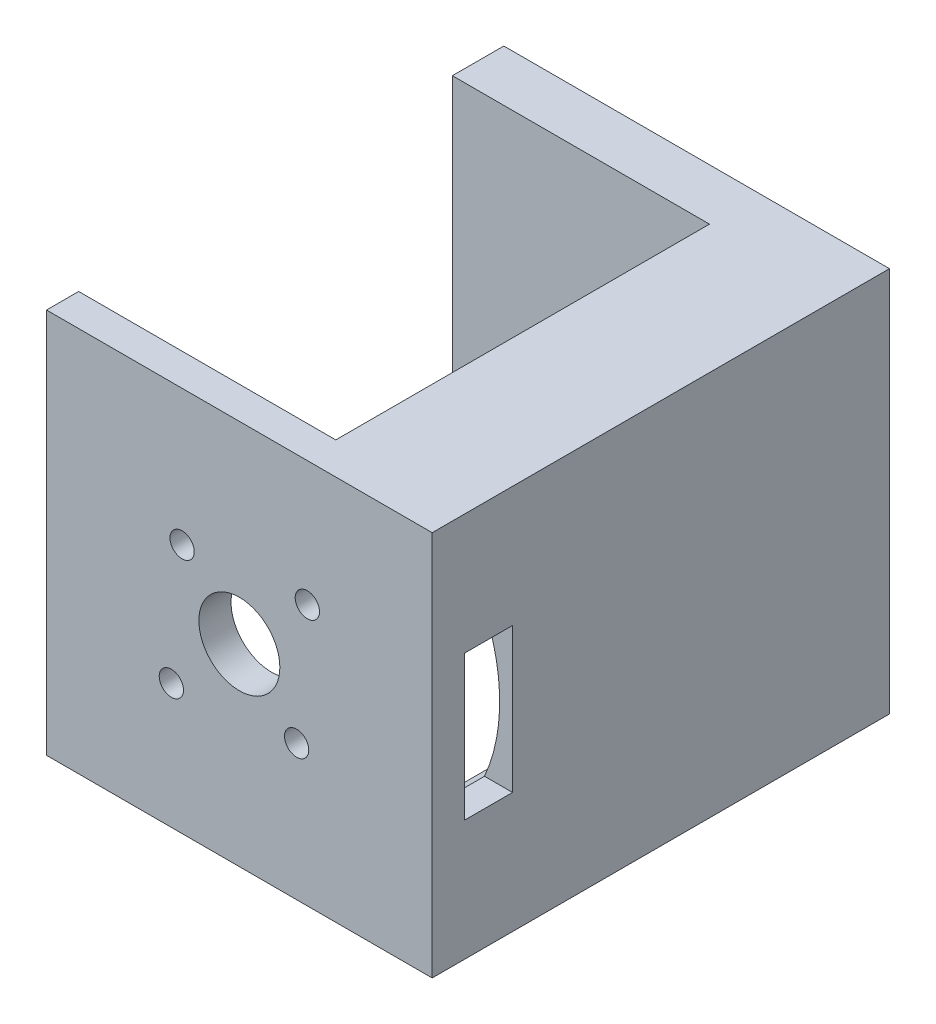
SolidWorks part; units mm, degrees
ref_plane "Front Plane" through (0, 0, 0) normal (0, 0, 1) x (1, 0, 0)
ref_plane "Top Plane" through (0, 0, 0) normal (0, 1, 0) x (1, 0, 0)
ref_plane "Right Plane" through (0, 0, 0) normal (1, 0, 0) x (0, 0, -1)
sketch "Sketch2" plane through (0, 0, 0) normal (0, 0, 1) x (1, 0, 0)
  line L0 (0, 0) -> (19.05, 0) construction
  line L1 (-19.05, 19.05) -> (19.05, 19.05)
  line L2 (-19.05, 19.05) -> (-19.05, -19.05)
  line L3 (-19.05, -19.05) -> (19.05, -19.05)
  line L4 (19.05, 19.05) -> (19.05, -19.05)
  line L5 (0, 0) -> (0, 19.05) construction
  arc A0 (5.5175, 6.7175) -> (7.9175, 6.7175) centre (6.7175, 6.7175) ccw construction
  arc A1 (7.9175, 6.7175) -> (5.5175, 6.7175) centre (6.7175, 6.7175) ccw construction
  arc A2 (4.4569, -5.6569) -> (6.8569, -5.6569) centre (5.6569, -5.6569) ccw construction
  arc A3 (6.8569, -5.6569) -> (4.4569, -5.6569) centre (5.6569, -5.6569) ccw construction
  arc A4 (-7.9175, -6.7175) -> (-5.5175, -6.7175) centre (-6.7175, -6.7175) ccw construction
  arc A5 (-5.5175, -6.7175) -> (-7.9175, -6.7175) centre (-6.7175, -6.7175) ccw construction
  arc A6 (-6.8569, 5.6569) -> (-4.4569, 5.6569) centre (-5.6569, 5.6569) ccw construction
  arc A7 (-4.4569, 5.6569) -> (-6.8569, 5.6569) centre (-5.6569, 5.6569) ccw construction
  arc A8 (5.5175, 6.7175) -> (7.9175, 6.7175) centre (6.7175, 6.7175) ccw
  arc A9 (7.9175, 6.7175) -> (5.5175, 6.7175) centre (6.7175, 6.7175) ccw
  arc A10 (4.4569, -5.6569) -> (6.8569, -5.6569) centre (5.6569, -5.6569) ccw
  arc A11 (6.8569, -5.6569) -> (4.4569, -5.6569) centre (5.6569, -5.6569) ccw
  arc A12 (-7.9175, -6.7175) -> (-5.5175, -6.7175) centre (-6.7175, -6.7175) ccw
  arc A13 (-5.5175, -6.7175) -> (-7.9175, -6.7175) centre (-6.7175, -6.7175) ccw
  arc A14 (-6.8569, 5.6569) -> (-4.4569, 5.6569) centre (-5.6569, 5.6569) ccw
  arc A15 (-4.4569, 5.6569) -> (-6.8569, 5.6569) centre (-5.6569, 5.6569) ccw
  arc A16 (0, -4) -> (0, 4) centre (0, 0) ccw
  arc A17 (0, -4) -> (0, 4) centre (0, 0) ccw
  arc A18 (0, 4) -> (0, -4) centre (0, 0) ccw
  arc A19 (0, 4) -> (0, -4) centre (0, 0) ccw
  dimension "D1" = 38.1
extrude "Boss-Extrude1" add sketch "Sketch2" along normal blind 3.175
sketch "Sketch3" plane through (0, 0, 0) normal (0, 0, -1) x (-1, 0, 0)
  line L0 (0, 0) -> (19.05, 0) construction
  line L1 (19.05, 19.05) -> (19.05, -19.05) construction
  line L2 (0, 0) -> (0, 19.05) construction
  line L3 (-19.05, 19.05) -> (19.05, 19.05) construction
  line L4 (19.05, -19.05) -> (-19.05, -19.05)
  line L5 (19.05, -19.05) -> (-19.05, -19.05)
  line L6 (-19.05, -19.05) -> (-19.05, 19.05)
  line L7 (-19.05, -19.05) -> (-19.05, 19.05)
  line L8 (-19.05, 19.05) -> (19.05, 19.05)
  line L9 (-19.05, 19.05) -> (19.05, 19.05)
  line L10 (19.05, 19.05) -> (19.05, -19.05)
  line L11 (19.05, 19.05) -> (19.05, -19.05)
  line L12 (-6.35, -16.6074) -> (-6.35, -19.05)
  line L13 (-6.35, 16.6074) -> (-6.35, 19.05)
  circle A0 centre (0, 0) radius 17.78
  line M6 (-19.05, 19.05) -> (-19.05, -19.05)
  line M7 (-19.05, -19.05) -> (19.05, -19.05)
  dimension "D2" = 35.56
  dimension "D1" = 19.05
  dimension "D3" = 6.35
extrude "Boss-Extrude2" add sketch "Sketch3" along normal offset from surface (36.92 mm away) 5.08 contours A0 L13 L9 L12 M6 M7
sketch "Sketch5" plane through (0, 0, -36.92) normal (0, 0, -1) x (-1, 0, 0)
  line L0 (19.05, -19.05) -> (-19.05, -19.05)
  line L1 (19.05, -19.05) -> (-19.05, -19.05)
  line L2 (-19.05, -19.05) -> (-19.05, 19.05)
  line L3 (-19.05, -19.05) -> (-19.05, 19.05)
  line L4 (-19.05, 19.05) -> (19.05, 19.05)
  line L5 (-19.05, 19.05) -> (19.05, 19.05)
  line L6 (19.05, 19.05) -> (19.05, -19.05)
  line L7 (19.05, 19.05) -> (19.05, -19.05)
  arc A0 (14, 0) -> (-14, 0) centre (0, 0) ccw
  arc A1 (14, 0) -> (-14, 0) centre (0, 0) ccw
  arc A2 (-14, 0) -> (14, 0) centre (0, 0) ccw
  arc A3 (-14, 0) -> (14, 0) centre (0, 0) ccw
  circle A4 centre (0, 0) radius 6.35
  arc M8 (-6.35, -16.6074) -> (-6.35, 16.6074) centre (0, 0) cw
  line M9 (-6.35, 16.6074) -> (-6.35, 19.05)
  line M10 (-6.35, 19.05) -> (-19.05, 19.05)
  line M11 (-19.05, 19.05) -> (-19.05, -19.05)
  line M12 (-19.05, -19.05) -> (-6.35, -19.05)
  line M13 (-6.35, -19.05) -> (-6.35, -16.6074)
  dimension "D1" = 12.7
extrude "Boss-Extrude3" add sketch "Sketch5" along normal blind 5.08 contours A1 A3 A4 | L7 L5 L1 A3 A1 M9 M8 M13 | M13 M8 M9 M10 M11 M12
sketch "Sketch8" plane through (19.05, 0, 0) normal (1, 0, 0) x (0, 0, -1)
  line L0 (4.7625, 7.1437) -> (4.7625, 19.05) construction
  line L1 (0, 7.1437) -> (4.7625, 7.1437)
  line L2 (0, 7.1437) -> (0, -7.1437)
  line L3 (0, -7.1437) -> (4.7625, -7.1437)
  line L4 (4.7625, 7.1437) -> (4.7625, -7.1437)
  line L5 (-3.175, 19.05) -> (42, 19.05) construction
  line L6 (4.7625, -7.1437) -> (4.7625, -19.05) construction
  line L7 (-3.175, -19.05) -> (42, -19.05) construction
  line L8 (-3.175, -19.05) -> (-3.175, 19.05) construction
  dimension "D1" = 3.175
  dimension "D2" = 14.2875
  dimension "D3" = 4.7625
extrude "Cut-Extrude1" cut sketch "Sketch8" against normal through all
